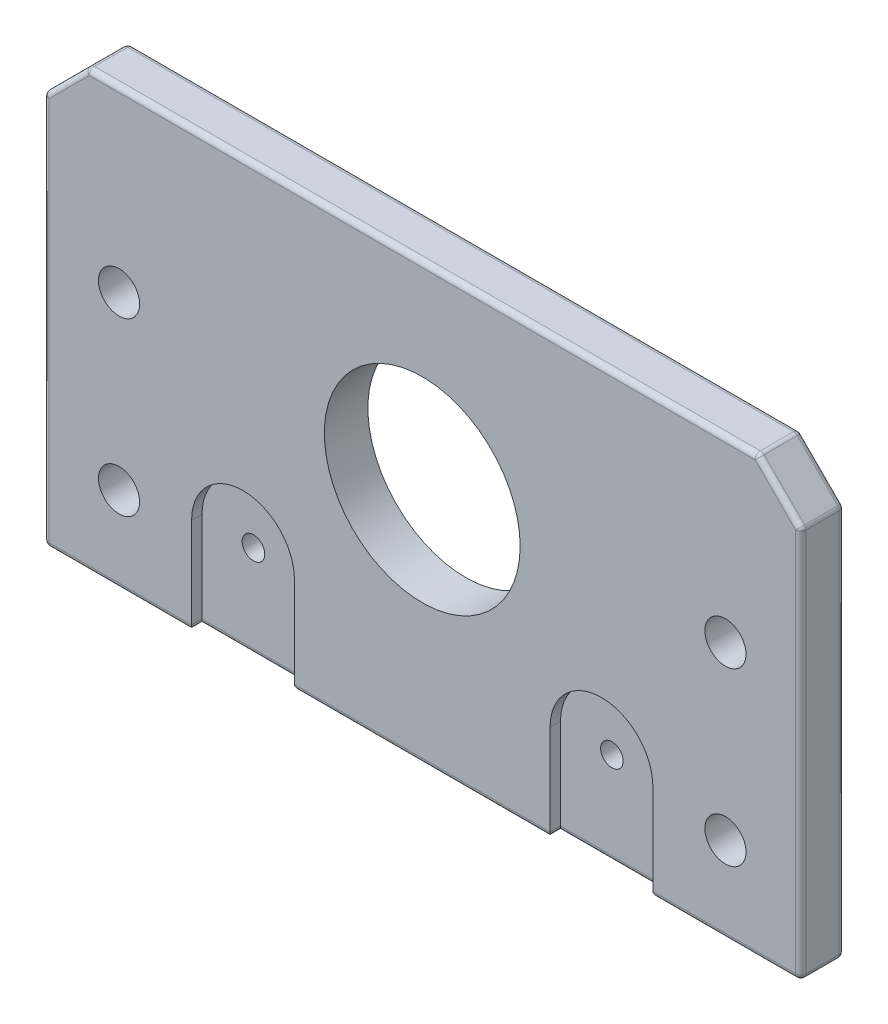
SolidWorks part; units mm, degrees
ref_plane "Front Plane" through (0, 0, 0) normal (0, 0, 1) x (1, 0, 0)
ref_plane "Top Plane" through (0, 0, 0) normal (0, 1, 0) x (1, 0, 0)
ref_plane "Right Plane" through (0, 0, 0) normal (1, 0, 0) x (0, 0, -1)
sketch "Sketch2" plane through (0, 0, 0) normal (0, 1, 0) x (1, 0, 0)
  line L1 (-55.245, 3.175) -> (55.245, 3.175)
  line L2 (-55.245, 3.175) -> (-55.245, -3.175)
  line L3 (-55.245, -3.175) -> (55.245, -3.175)
  line L4 (55.245, 3.175) -> (55.245, -3.175)
  point P4 (0, 3.175)
  point P7 (-55.245, 0)
  dimension "D1" = 6.35
  dimension "D2" = 110.49
extrude "Boss-Extrude1" add sketch "Sketch2" against normal blind 63.5
sketch "Sketch3" plane through (0, 0, 3.175) normal (0, 0, 1) x (1, 0, 0)
  line L2 (-55.245, 0) -> (55.245, 0) construction
  circle A0 centre (0, -28.815) radius 14.2875
  point P2 (0, 0)
  dimension "D1" = 28.815
  dimension "D3" = 28.575
extrude "Cut-Extrude1" cut sketch "Sketch3" against normal through all
chamfer "Chamfer1" distance 6.35 angle 45 2 edges at (-55.245, 0, 0) (55.245, 0, 0)
fillet "Fillet1" [suppressed] radius 0.762
hole_wizard "CBORE for M4 SHCS2" [suppressed] positions "Sketch9" profile "Sketch10" counterbore size "M4" standard "ANSI Metric"
sketch "Sketch9" [suppressed] plane through (0, 0, 3.175) normal (0, 0, 1) x (1, 0, 0)
  line L0 (-48.5794, 0) -> (48.5794, 0) construction
  line L1 (-55.245, -62.738) -> (-55.245, -6.6656) construction
  point P0 (-17.9605, -10.8545)
  dimension "D1" = 10.8545
  dimension "D2" = 37.2845
sketch "Sketch10" plane through (-17.9605, -10.8545, 3.175) normal (1, 0, 0) x (0, -1, 0)
  line L0 (0, 0) -> (0, 6.35)
  line L1 (0, 6.35) -> (2.25, 6.35)
  line L3 (2.25, 6.35) -> (2.25, 4)
  line L4 (2.25, 4) -> (4, 4)
  line L5 (4, 4) -> (4, 0)
  line L7 (4, 0) -> (0, 0)
  line L11 (0, -6.35) -> (0, 107.95) construction
  dimension "Thru Hole Dia." = 4.5
  dimension "Thru Hole Depth" = 6.35
  dimension "C'Bore Dia." = 8
  dimension "C'Bore Depth" = 4
sketch "Sketch12" plane through (0, 0, 3.175) normal (0, 0, 1) x (1, 0, 0)
  line L0 (-33.655, -49.5) -> (-33.655, -63.5)
  line L1 (-55.245, -63.5) -> (-55.245, -6.35) construction
  line L2 (-33.655, -63.5) -> (-18.655, -63.5)
  line L3 (-55.245, -63.5) -> (55.245, -63.5) construction
  line L5 (-18.655, -63.5) -> (-18.655, -49.5)
  arc A0 (-18.655, -49.5) -> (-33.655, -49.5) centre (-26.155, -49.5) ccw
  point P3 (-33.655, -63.5)
  point P7 (0, 0)
  point P9 (-33.655, -49.5)
  point P10 (0, 0)
  dimension "D4" = 7.5
  dimension "D1" = 14
  dimension "D2" = 15
  dimension "D3" = 14
  dimension "D5" = 29.09
extrude "Cut-Extrude2" cut sketch "Sketch12" against normal blind 1.524
mirror "Mirror1" about plane through (0, 0, 0) normal (1, 0, 0) of "Cut-Extrude2"
hole_wizard "Tap Drill for M4x0.7 Tap1" positions "Sketch13" profile "Sketch14" hole size "M4x0.7" standard "ANSI Metric" end condition through all
sketch "Sketch13" plane through (0, 0, 3.175) normal (0, 0, 1) x (1, 0, 0)
  line L1 (0, -3.4925) -> (0, 3.4925) construction
  line L2 (-48.895, 0) -> (48.895, 0) construction
  point P0 (-26.155, -50)
  point P3 (26.155, -50)
  dimension "D1" = 52.31
  dimension "D2" = 26.155
  dimension "D3" = 50
sketch "Sketch14" plane through (-26.155, -50, 3.175) normal (1, 0, 0) x (0, -1, 0)
  line L0 (0, 0) -> (0, 6.35)
  line L1 (0, 6.35) -> (1.65, 6.35)
  line L2 (1.65, 6.35) -> (1.65, 0)
  line L5 (1.65, 0) -> (0, 0)
  line L11 (0, -6.35) -> (0, 107.95) construction
  dimension "Thru Hole Dia." = 3.3
  dimension "Thru Hole Depth" = 6.35
hole_wizard "Tap Drill for M7x1.0 Tap1" positions "Sketch17" profile "Sketch16" hole size "M7x1.0" standard "ANSI Metric" end condition through all
sketch "Sketch17" plane through (0, 0, -3.175) normal (0, 0, -1) x (-1, 0, 0)
  line L0 (0, 3.4925) -> (0, -3.4925) construction
  line L1 (-48.895, 0) -> (48.895, 0) construction
  point P0 (44.245, -26)
  point P3 (44.245, -51)
  point P6 (-44.245, -51)
  point P9 (-44.245, -26)
  dimension "D1" = 25
  dimension "D2" = 25
  dimension "D3" = 88.49
  dimension "D4" = 44.245
  dimension "D5" = 26
sketch "Sketch16" plane through (-44.245, -26, -3.175) normal (1, 0, 0) x (0, 1, 0)
  line L0 (0, 0) -> (0, 6.35)
  line L1 (0, 6.35) -> (3, 6.35)
  line L2 (3, 6.35) -> (3, 0)
  line L5 (3, 0) -> (0, 0)
  line L11 (0, -6.35) -> (0, 107.95) construction
  dimension "Thru Hole Dia." = 6
  dimension "Thru Hole Depth" = 6.35
fillet "Fillet2" radius 0.762 26 edges at (44.45, -63.5, 3.175) (0, -63.5, -3.175) (-44.45, -63.5, 3.175) (-33.655, -63.5, 2.413) (-26.155, -63.5, 1.651) (-18.655, -63.5, 2.413) (0, -63.5, 3.175) (18.655, -63.5, 2.413) (26.155, -63.5, 1.651) (33.655, -63.5, 2.413) (55.245, -63.5, 0) (55.245, -34.925, 3.175) (55.245, -34.925, -3.175) (52.07, -3.175, -3.175) (55.245, -6.35, 0) (52.07, -3.175, 3.175) (48.895, 0, 0) (0, 0, 3.175) (0, 0, -3.175) (-48.895, 0, 0) (-52.07, -3.175, 3.175) (-52.07, -3.175, -3.175) (-55.245, -63.5, 0) (-55.245, -34.925, -3.175) (-55.245, -6.35, 0) (-55.245, -34.925, 3.175)
